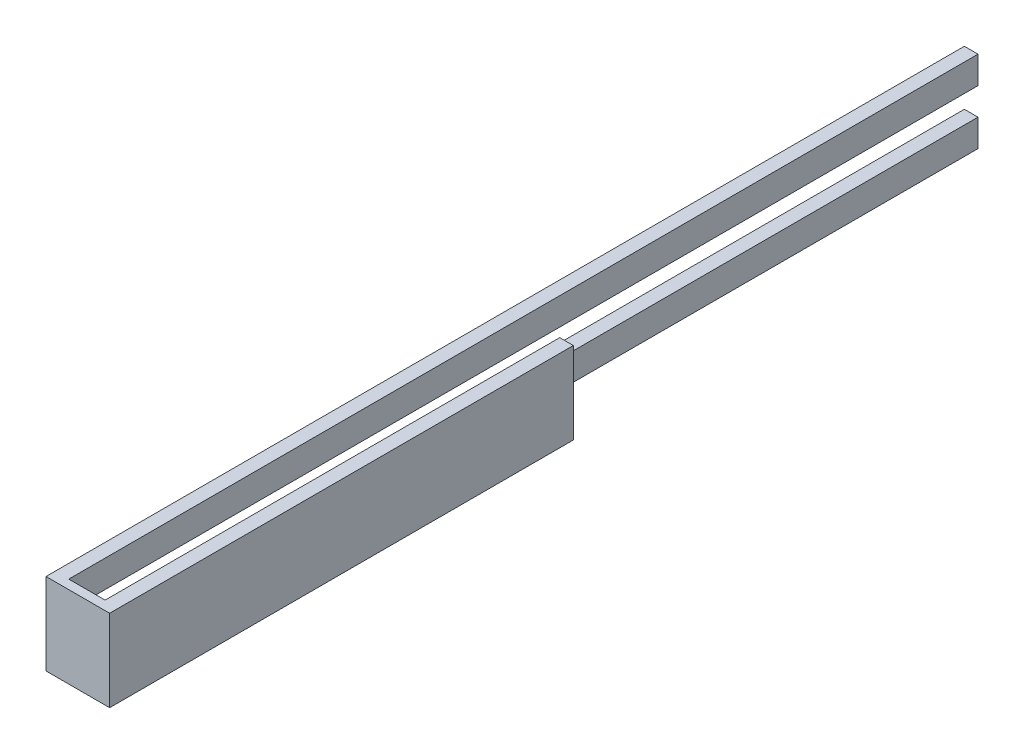
SolidWorks part; units mm, degrees
ref_plane "Front Plane" through (0, 0, 0) normal (0, 0, 1) x (1, 0, 0)
ref_plane "Top Plane" through (0, 0, 0) normal (0, 1, 0) x (1, 0, 0)
ref_plane "Right Plane" through (0, 0, 0) normal (1, 0, 0) x (0, 0, -1)
sketch "Sketch1" plane through (0, 0, 0) normal (0, 0, 1) x (1, 0, 0)
  line L1 (0, 0) -> (6, 0)
  line L2 (0, 0) -> (0, 9)
  line L3 (0, 9) -> (6, 9)
  line L4 (6, 0) -> (6, 9)
  dimension "D1" = 6
  dimension "D2" = 9
extrude "Boss-Extrude1" add sketch "Sketch1" along normal blind 1
sketch "Sketch2" plane through (0, 0, 0) normal (0, 0, -1) x (-1, 0, 0)
  line L1 (0, 0) -> (-1, 0)
  line L2 (0, 0) -> (0, 3)
  line L3 (0, 3) -> (-1, 3)
  line L4 (-1, 0) -> (-1, 3)
  line L5 (0, 9) -> (-1, 9)
  line L6 (0, 9) -> (0, 6)
  line L7 (0, 6) -> (-1, 6)
  line L8 (-1, 9) -> (-1, 6)
  line L9 (-6, 9) -> (-5, 9)
  line L10 (-6, 9) -> (-6, 6)
  line L11 (-6, 6) -> (-5, 6)
  line L12 (-5, 9) -> (-5, 6)
  line L17 (-6, 0) -> (-6, 9) construction
  line L18 (-6, 0) -> (-5, 0)
  line L19 (-6, 0) -> (-6, 3)
  line L20 (-6, 3) -> (-5, 3)
  line L21 (-5, 0) -> (-5, 3)
  dimension "D1" = 1
  dimension "D2" = 3
  dimension "D3" = 1
  dimension "D4" = 1
  dimension "D5" = 3
  dimension "D6" = 3
  dimension "D7" = 1
  dimension "D8" = 3
extrude "Boss-Extrude2" add sketch "Sketch2" along normal blind 100 contours L2 L1 L4 L3 | L6 L5 L8 L7
sketch "Sketch3" plane through (0, 0, 0) normal (0, 0, -1) x (-1, 0, 0)
  line L0 (-1, 0) -> (-6, 0) construction
  line L1 (-6, 9) -> (-5, 9)
  line L2 (-6, 9) -> (-6, 0)
  line L3 (-6, 0) -> (-5, 0)
  line L4 (-5, 9) -> (-5, 0)
  dimension "D1" = 1
extrude "Boss-Extrude3" add sketch "Sketch3" along normal blind 50
sketch "Sketch4" plane through (6, 0, 0) normal (1, 0, 0) x (0, 0, -1)
  line L4 (-1, 0) -> (50, 0)
  line L5 (50, 0) -> (50, 9)
  line L6 (50, 9) -> (-1, 9)
  line L7 (-1, 9) -> (-1, 0)
  line L8 (-1, 0) -> (50, 0)
  line L9 (50, 0) -> (50, 9)
  line L10 (50, 9) -> (-1, 9)
  line L11 (-1, 9) -> (-1, 0)
  dimension "D1" = 0
extrude "Boss-Extrude4" add sketch "Sketch4" along normal blind 0.5
sketch "Sketch5" plane through (0, 0, 0) normal (-1, 0, 0) x (0, 0, 1)
  line L8 (1, 9) -> (-100, 9)
  line L9 (-100, 9) -> (-100, 6)
  line L10 (-100, 6) -> (0, 6)
  line L11 (0, 6) -> (0, 3)
  line L12 (0, 3) -> (-100, 3)
  line L13 (-100, 3) -> (-100, 0)
  line L14 (-100, 0) -> (1, 0)
  line L15 (1, 0) -> (1, 9)
  line L16 (1, 9) -> (-100, 9)
  line L17 (-100, 9) -> (-100, 6)
  line L18 (-100, 6) -> (0, 6)
  line L19 (0, 6) -> (0, 3)
  line L20 (0, 3) -> (-100, 3)
  line L21 (-100, 3) -> (-100, 0)
  line L22 (-100, 0) -> (1, 0)
  line L23 (1, 0) -> (1, 9)
  dimension "D1" = 0
extrude "Boss-Extrude5" add sketch "Sketch5" along normal blind 0.5
